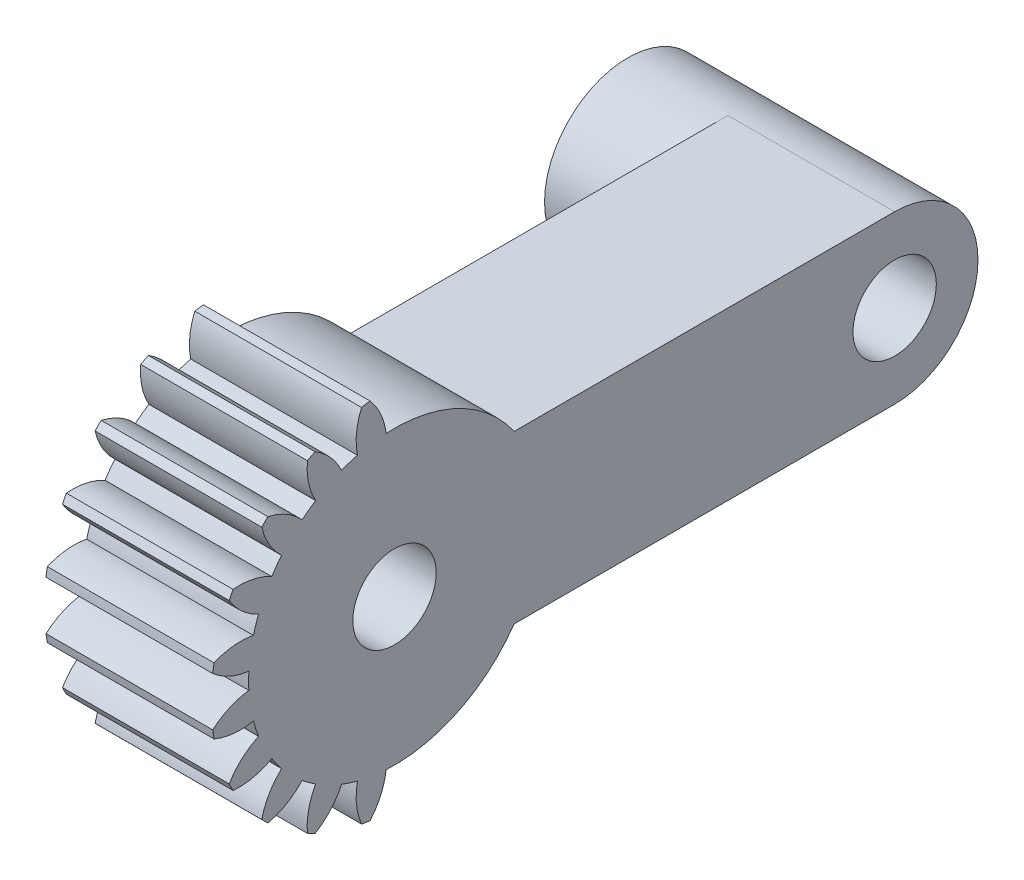
SolidWorks part; units mm, degrees
ref_plane "Front Plane" through (0, 0, 0) normal (0, 0, 1) x (1, 0, 0)
ref_plane "Top Plane" through (0, 0, 0) normal (0, 1, 0) x (1, 0, 0)
ref_plane "Right Plane" through (0, 0, 0) normal (1, 0, 0) x (0, 0, -1)
ref_plane "Plane1" through (4.0439, 0, 0) normal (1, 0, 0) x (0, 0, -1)
sketch "Sketch1" plane through (4.0439, 0, 0) normal (1, 0, 0) x (0, 0, -1)
  circle A0 centre (0.8725, -1.1221) radius 2.5
  arc A1 (-10.0295, 0.3429) -> (-7.8622, -0.6222) centre (-7.392, 3.3501) ccw
  arc A2 (-7.8622, -0.6222) -> (-7.8622, -1.622) centre (0.8725, -1.1221) ccw
  arc A3 (-7.8622, -1.622) -> (-10.0295, -2.587) centre (-7.392, -5.5943) ccw
  arc A4 (-10.0295, -2.587) -> (-9.9487, -3.0977) centre (0.8725, -1.1221) ccw
  arc A5 (-9.9487, -3.0977) -> (-7.5892, -3.3458) centre (-8.3695, 0.5774) ccw
  arc A6 (-7.5892, -3.3458) -> (-7.2802, -4.2967) centre (0.8725, -1.1221) ccw
  arc A7 (-7.2802, -4.2967) -> (-9.0433, -5.8842) centre (-5.6055, -7.9292) ccw
  arc A8 (-9.0433, -5.8842) -> (-8.8085, -6.3449) centre (0.8725, -1.1221) ccw
  arc A9 (-8.8085, -6.3449) -> (-6.4879, -5.8518) centre (-8.4423, -2.3617) ccw
  arc A10 (-6.4879, -5.8518) -> (-5.9002, -6.6607) centre (0.8725, -1.1221) ccw
  arc A11 (-5.9002, -6.6607) -> (-7.0864, -8.7153) centre (-3.185, -9.5979) ccw
  arc A12 (-7.0864, -8.7153) -> (-6.7207, -9.0809) centre (0.8725, -1.1221) ccw
  arc A13 (-6.7207, -9.0809) -> (-4.6661, -7.8948) centre (-7.6033, -5.1795) ccw
  arc A14 (-4.6661, -7.8948) -> (-3.8572, -8.4825) centre (0.8725, -1.1221) ccw
  arc A15 (-3.8572, -8.4825) -> (-4.3504, -10.8031) centre (-0.3672, -10.4369) ccw
  arc A16 (-4.3504, -10.8031) -> (-3.8897, -11.0378) centre (0.8725, -1.1221) ccw
  arc A17 (-3.8897, -11.0378) -> (-2.3022, -9.2748) centre (-5.9347, -7.6001) ccw
  arc A18 (-2.3022, -9.2748) -> (-1.3512, -9.5838) centre (0.8725, -1.1221) ccw
  arc A19 (-1.3512, -9.5838) -> (-1.1032, -11.9432) centre (2.5719, -10.3641) ccw
  arc A20 (-1.1032, -11.9432) -> (-0.5925, -12.0241) centre (0.8725, -1.1221) ccw
  arc A21 (-0.5925, -12.0241) -> (0.3725, -9.8568) centre (-3.5997, -9.3866) ccw
  arc A22 (0.3725, -9.8568) -> (1.3724, -9.8568) centre (0.8725, -1.1221) ccw
  arc A23 (1.3724, -9.8568) -> (2.3374, -12.0241) centre (5.3447, -9.3866) ccw
  arc A24 (2.3374, -12.0241) -> (2.8481, -11.9432) centre (0.8725, -1.1221) ccw
  arc A25 (2.8481, -11.9432) -> (3.0962, -9.5838) centre (-0.827, -10.3641) ccw
  arc A26 (3.0962, -9.5838) -> (4.0471, -9.2748) centre (0.8725, -1.1221) ccw
  arc A27 (4.0471, -9.2748) -> (5.6346, -11.0378) centre (7.6796, -7.6001) ccw
  arc A28 (5.6346, -11.0378) -> (6.0953, -10.8031) centre (0.8725, -1.1221) ccw
  arc A29 (6.0953, -10.8031) -> (5.6022, -8.4825) centre (2.1121, -10.4369) ccw
  arc A30 (5.6022, -8.4825) -> (6.411, -7.8948) centre (0.8725, -1.1221) ccw
  arc A31 (6.411, -7.8948) -> (8.4657, -9.0809) centre (9.3483, -5.1795) ccw
  arc A32 (8.4657, -9.0809) -> (8.8313, -8.7153) centre (0.8725, -1.1221) ccw
  arc A33 (8.8313, -8.7153) -> (7.6451, -6.6607) centre (4.9299, -9.5979) ccw
  arc A34 (7.6451, -6.6607) -> (8.2328, -5.8518) centre (0.8725, -1.1221) ccw
  arc A35 (8.2328, -5.8518) -> (10.5535, -6.3449) centre (10.1873, -2.3617) ccw
  arc A36 (10.5535, -6.3449) -> (10.7882, -5.8842) centre (0.8725, -1.1221) ccw
  arc A37 (10.7882, -5.8842) -> (9.0252, -4.2967) centre (7.3505, -7.9292) ccw
  arc A38 (9.0252, -4.2967) -> (9.3342, -3.3458) centre (0.8725, -1.1221) ccw
  arc A39 (9.3342, -3.3458) -> (11.6936, -3.0977) centre (10.1144, 0.5774) ccw
  arc A40 (11.6936, -3.0977) -> (11.7745, -2.587) centre (0.8725, -1.1221) ccw
  arc A41 (11.7745, -2.587) -> (9.6072, -1.622) centre (9.137, -5.5943) ccw
  arc A42 (9.6072, -1.622) -> (9.6072, -0.6222) centre (0.8725, -1.1221) ccw
  arc A43 (9.6072, -0.6222) -> (11.7745, 0.3429) centre (9.137, 3.3501) ccw
  arc A44 (11.7745, 0.3429) -> (11.6936, 0.8536) centre (0.8725, -1.1221) ccw
  arc A45 (11.6936, 0.8536) -> (9.3342, 1.1016) centre (10.1144, -2.8215) ccw
  arc A46 (9.3342, 1.1016) -> (9.0252, 2.0526) centre (0.8725, -1.1221) ccw
  arc A47 (9.0252, 2.0526) -> (10.7882, 3.6401) centre (7.3505, 5.6851) ccw
  arc A48 (10.7882, 3.6401) -> (10.5535, 4.1008) centre (0.8725, -1.1221) ccw
  arc A49 (10.5535, 4.1008) -> (8.2328, 3.6076) centre (10.1873, 0.1176) ccw
  arc A50 (8.2328, 3.6076) -> (7.6451, 4.4165) centre (0.8725, -1.1221) ccw
  arc A51 (7.6451, 4.4165) -> (8.8313, 6.4711) centre (4.9299, 7.3537) ccw
  arc A52 (8.8313, 6.4711) -> (8.4657, 6.8368) centre (0.8725, -1.1221) ccw
  arc A53 (8.4657, 6.8368) -> (6.411, 5.6506) centre (9.3483, 2.9353) ccw
  arc A54 (6.411, 5.6506) -> (5.6022, 6.2383) centre (0.8725, -1.1221) ccw
  arc A55 (5.6022, 6.2383) -> (6.0953, 8.5589) centre (2.1121, 8.1927) ccw
  arc A56 (6.0953, 8.5589) -> (5.6346, 8.7937) centre (0.8725, -1.1221) ccw
  arc A57 (5.6346, 8.7937) -> (4.0471, 7.0306) centre (7.6796, 5.3559) ccw
  arc A58 (4.0471, 7.0306) -> (3.0962, 7.3396) centre (0.8725, -1.1221) ccw
  arc A59 (3.0962, 7.3396) -> (2.8481, 9.6991) centre (-0.827, 8.1199) ccw
  arc A60 (2.8481, 9.6991) -> (2.3374, 9.7799) centre (0.8725, -1.1221) ccw
  arc A61 (2.3374, 9.7799) -> (1.3724, 7.6126) centre (5.3447, 7.1424) ccw
  arc A62 (1.3724, 7.6126) -> (0.3725, 7.6126) centre (0.8725, -1.1221) ccw
  arc A63 (0.3725, 7.6126) -> (-0.5925, 9.7799) centre (-3.5997, 7.1424) ccw
  arc A64 (-0.5925, 9.7799) -> (-1.1032, 9.6991) centre (0.8725, -1.1221) ccw
  arc A65 (-1.1032, 9.6991) -> (-1.3512, 7.3396) centre (2.5719, 8.1199) ccw
  arc A66 (-1.3512, 7.3396) -> (-2.3022, 7.0306) centre (0.8725, -1.1221) ccw
  arc A67 (-2.3022, 7.0306) -> (-3.8897, 8.7937) centre (-5.9347, 5.3559) ccw
  arc A68 (-3.8897, 8.7937) -> (-4.3504, 8.5589) centre (0.8725, -1.1221) ccw
  arc A69 (-4.3504, 8.5589) -> (-3.8572, 6.2383) centre (-0.3672, 8.1927) ccw
  arc A70 (-3.8572, 6.2383) -> (-4.6661, 5.6506) centre (0.8725, -1.1221) ccw
  arc A71 (-4.6661, 5.6506) -> (-6.7207, 6.8368) centre (-7.6033, 2.9353) ccw
  arc A72 (-6.7207, 6.8368) -> (-7.0864, 6.4711) centre (0.8725, -1.1221) ccw
  arc A73 (-7.0864, 6.4711) -> (-5.9002, 4.4165) centre (-3.185, 7.3537) ccw
  arc A74 (-5.9002, 4.4165) -> (-6.4879, 3.6076) centre (0.8725, -1.1221) ccw
  arc A75 (-6.4879, 3.6076) -> (-8.8085, 4.1008) centre (-8.4423, 0.1176) ccw
  arc A76 (-8.8085, 4.1008) -> (-9.0433, 3.6401) centre (0.8725, -1.1221) ccw
  arc A77 (-9.0433, 3.6401) -> (-7.2802, 2.0526) centre (-5.6055, 5.6851) ccw
  arc A78 (-7.2802, 2.0526) -> (-7.5892, 1.1016) centre (0.8725, -1.1221) ccw
  arc A79 (-7.5892, 1.1016) -> (-9.9487, 0.8536) centre (-8.3695, -2.8215) ccw
  arc A80 (-9.9487, 0.8536) -> (-10.0295, 0.3429) centre (0.8725, -1.1221) ccw
extrude "Boss-Extrude1" add sketch "Sketch1" against normal blind 10
sketch "Sketch2" plane through (4.0439, 0, 0) normal (1, 0, 0) x (0, 0, -1)
  line L0 (0.8725, -1.1221) -> (30.8725, -1.1221) construction
  line L1 (0.8725, 3.8779) -> (30.8725, 3.8779)
  line L2 (0.8725, -6.1221) -> (30.8725, -6.1221)
  arc A0 (0.8725, 3.8779) -> (0.8725, -6.1221) centre (0.8725, -1.1221) ccw
  arc A1 (30.8725, -6.1221) -> (30.8725, 3.8779) centre (30.8725, -1.1221) ccw
  arc A2 (35.8678, -1.3374) -> (35.8678, -0.9067) centre (30.8725, -1.1221) ccw
  circle A3 centre (30.8725, -1.1221) radius 2.5
  point P3 (15.8725, -1.1221)
  dimension "D2" = 5
  dimension "D1" = 10
  dimension "D3" = 30
extrude "Boss-Extrude2" add sketch "Sketch2" against normal blind 10
sketch "Sketch3" plane through (-5.9561, 0, 0) normal (-1, 0, 0) x (0, 0, 1)
  circle A0 centre (-30.8725, -1.1221) radius 2.5
  circle A1 centre (-30.8725, -1.1221) radius 5
extrude "Boss-Extrude3" add sketch "Sketch3" along normal blind 6
sketch "Sketch4" plane through (4.0439, 0, 0) normal (1, 0, 0) x (0, 0, -1)
  circle A1 centre (0.8725, -1.1221) radius 2.5
  dimension "D1" = 5
extrude "Cut-Extrude1" cut sketch "Sketch4" against normal blind 5
sketch "Sketch5" plane through (4.0439, 0, 0) normal (1, 0, 0) x (0, 0, -1)
  circle A0 centre (0.8725, -1.1221) radius 9.5637
sketch "Sketch6" plane through (-0.9561, 0, 0) normal (1, 0, 0) x (0, 0, -1)
  circle A0 centre (0.8725, -1.1221) radius 1.5
  dimension "D1" = 3
extrude "Cut-Extrude2" cut sketch "Sketch6" against normal through all
sketch "Sketch7" plane through (-5.9561, 0, 0) normal (-1, 0, 0) x (0, 0, 1)
  circle A0 centre (-0.8725, -1.1221) radius 2.5
  dimension "D1" = 5
extrude "Cut-Extrude3" cut sketch "Sketch7" against normal blind 3
sketch "Sketch8" plane through (-5.9561, 0, 0) normal (-1, 0, 0) x (0, 0, 1)
  circle A0 centre (-0.8725, -1.1221) radius 2.5
  circle A1 centre (-0.8725, -1.1221) radius 4.5
  dimension "D1" = 2
  dimension "D2" = 5
extrude "Boss-Extrude4" add sketch "Sketch8" along normal blind 2
sketch "Sketch9" plane through (4.0439, 0, 0) normal (1, 0, 0) x (0, 0, -1)
  line L0 (11.3023, -6.1221) -> (8.052, -6.1221)
  line L2 (11.3023, 3.8779) -> (8.052, 3.8779)
  line L4 (0.8725, 7.6269) -> (0.8725, 10.4444)
  line L5 (0.8725, -9.8711) -> (0.8725, -12.6885)
  arc A0 (0.8725, -9.8711) -> (8.052, -6.1221) centre (0.8725, -1.1221) ccw
  arc A1 (0.8725, -12.6885) -> (11.3023, -6.1221) centre (0.8725, -1.1221) ccw
  arc A2 (11.3023, 3.8779) -> (0.8725, 10.4444) centre (0.8725, -1.1221) ccw
  arc A3 (8.052, 3.8779) -> (0.8725, 7.6269) centre (0.8725, -1.1221) ccw
extrude "Cut-Extrude4" cut sketch "Sketch9" against normal through all
